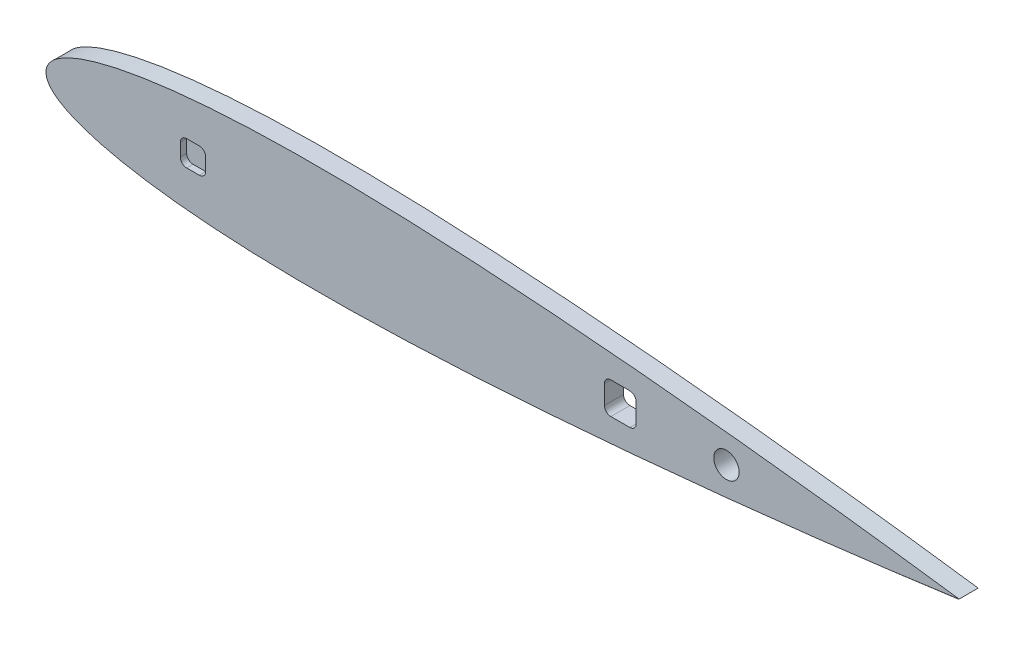
SolidWorks part; units mm, degrees
ref_plane "Plano frontal" through (0, 0, 0) normal (0, 0, 1) x (1, 0, 0)
ref_plane "Plano superior" through (0, 0, 0) normal (0, 1, 0) x (1, 0, 0)
ref_plane "Plano direito" through (0, 0, 0) normal (1, 0, 0) x (0, 0, -1)
curve "3"
  spline degree 3 poles (285.8178, -0.2472, 0) (289.2733, 0, 0) (285.8178, 0.2472, 0) (284.7679, 0.3981, 0) (284.2644, 0.4678, 0) (283.4377, 0.5838, 0) (282.2778, 0.7451, 0) (280.7932, 0.9499, 0) (278.9851, 1.1985, 0) (276.8584, 1.4881, 0) (274.4179, 1.8169, 0) (271.6694, 2.1836, 0) (268.6193, 2.5853, 0) (265.2747, 3.0204, 0) (261.6434, 3.4852, 0) (257.7338, 3.9787, 0) (253.5551, 4.4973, 0) (249.1172, 5.0383, 0) (244.4303, 5.5995, 0) (239.5054, 6.1777, 0) (234.3538, 6.7696, 0) (228.9879, 7.3736, 0) (223.4199, 7.9855, 0) (217.6632, 8.6035, 0) (211.7309, 9.2233, 0) (205.637, 9.8437, 0) (199.3956, 10.4599, 0) (193.0214, 11.07, 0) (186.5293, 11.6697, 0) (179.9344, 12.2571, 0) (173.2521, 12.8274, 0) (166.4979, 13.3779, 0) (159.6878, 13.9052, 0) (152.8376, 14.4051, 0) (145.9633, 14.8743, 0) (139.0811, 15.3092, 0) (132.2068, 15.7055, 0) (125.3566, 16.0601, 0) (118.5464, 16.3692, 0) (111.7921, 16.6293, 0) (105.1096, 16.8375, 0) (98.5145, 16.9901, 0) (92.0222, 17.0845, 0) (85.6476, 17.1179, 0) (79.4058, 17.0883, 0) (73.3113, 16.9946, 0) (67.3786, 16.8337, 0) (61.6212, 16.6065, 0) (56.0527, 16.3113, 0) (50.6859, 15.9489, 0) (45.5336, 15.5194, 0) (40.6077, 15.0237, 0) (35.9196, 14.4634, 0) (31.4802, 13.841, 0) (27.2999, 13.1577, 0) (23.3883, 12.4167, 0) (19.7544, 11.6209, 0) (16.4067, 10.7731, 0) (13.3526, 9.8769, 0) (10.5989, 8.9355, 0) (8.1513, 7.9519, 0) (6.0147, 6.9291, 0) (4.1933, 5.8692, 0) (2.6891, 4.774, 0) (1.5051, 3.6417, 0) (0.644, 2.4691, 0) (0.1176, 1.2504, 0) (-0.0573, 0, 0) (0.1176, -1.2504, 0) (0.644, -2.4691, 0) (1.5051, -3.6417, 0) (2.6891, -4.774, 0) (4.1933, -5.8692, 0) (6.0147, -6.9291, 0) (8.1513, -7.9519, 0) (10.5989, -8.9355, 0) (13.3526, -9.8769, 0) (16.4067, -10.7731, 0) (19.7544, -11.6209, 0) (23.3883, -12.4167, 0) (27.2999, -13.1577, 0) (31.4802, -13.841, 0) (35.9196, -14.4634, 0) (40.6077, -15.0237, 0) (45.5336, -15.5194, 0) (50.6859, -15.9489, 0) (56.0527, -16.3113, 0) (61.6212, -16.6065, 0) (67.3786, -16.8337, 0) (73.3113, -16.9946, 0) (79.4058, -17.0883, 0) (85.6476, -17.1179, 0) (92.0222, -17.0845, 0) (98.5145, -16.9901, 0) (105.1096, -16.8375, 0) (111.7921, -16.6293, 0) (118.5464, -16.3692, 0) (125.3566, -16.0601, 0) (132.2068, -15.7055, 0) (139.0811, -15.3092, 0) (145.9633, -14.8743, 0) (152.8376, -14.4051, 0) (159.6878, -13.9052, 0) (166.4979, -13.3779, 0) (173.2521, -12.8274, 0) (179.9344, -12.2571, 0) (186.5293, -11.6697, 0) (193.0214, -11.07, 0) (199.3956, -10.4599, 0) (205.637, -9.8437, 0) (211.7309, -9.2233, 0) (217.6632, -8.6035, 0) (223.4199, -7.9855, 0) (228.9879, -7.3736, 0) (234.3538, -6.7696, 0) (239.5054, -6.1777, 0) (244.4303, -5.5995, 0) (249.1172, -5.0383, 0) (253.5551, -4.4973, 0) (257.7338, -3.9787, 0) (261.6434, -3.4852, 0) (265.2747, -3.0204, 0) (268.6193, -2.5853, 0) (271.6694, -2.1836, 0) (274.4179, -1.8169, 0) (276.8584, -1.4881, 0) (278.9851, -1.1985, 0) (280.7932, -0.9499, 0) (282.2778, -0.7451, 0) (283.4377, -0.5838, 0) (284.2644, -0.4678, 0) (284.7679, -0.3981, 0) (285.8178, -0.2472, 0) (289.2733, 0, 0) (285.8178, 0.2472, 0) knots -0.00555 -0.004691 -0.004405 0 0.004405 0.004691 0.00555 0.00698 0.008976 0.011535 0.014649 0.018312 0.022515 0.027248 0.032498 0.038254 0.044502 0.051227 0.058413 0.066043 0.074099 0.082562 0.091412 0.100627 0.110187 0.120068 0.130247 0.140701 0.151404 0.162332 0.173459 0.184758 0.196204 0.207769 0.219426 0.231148 0.242906 0.254675 0.266426 0.278132 0.289766 0.301302 0.312712 0.323969 0.33505 0.345929 0.356581 0.366982 0.37711 0.386942 0.396458 0.405637 0.414459 0.422907 0.430963 0.438612 0.445838 0.45263 0.458976 0.464866 0.470294 0.475255 0.479749 0.483781 0.487363 0.490516 0.493279 0.495712 0.49791 0.5 0.50209 0.504288 0.506721 0.509484 0.512637 0.516219 0.520251 0.524745 0.529706 0.535134 0.541024 0.54737 0.554162 0.561388 0.569037 0.577093 0.585541 0.594363 0.603542 0.613058 0.62289 0.633018 0.643419 0.654071 0.66495 0.676031 0.687288 0.698698 0.710234 0.721868 0.733574 0.745325 0.757094 0.768852 0.780574 0.792231 0.803796 0.815242 0.826541 0.837668 0.848596 0.859299 0.869753 0.879932 0.889813 0.899373 0.908588 0.917438 0.925901 0.933957 0.941587 0.948773 0.955498 0.961746 0.967502 0.972752 0.977485 0.981688 0.985351 0.988465 0.991024 0.99302 0.99445 0.995309 0.995595 1 1.004405 1.004691 1.00555 periodic
curve "4"
  spline degree 3 poles (254.7117, -0.2203, 0) (257.7912, 0, 0) (254.7117, 0.2203, 0) (253.7761, 0.3548, 0) (253.3275, 0.4169, 0) (252.5907, 0.5202, 0) (251.5571, 0.664, 0) (250.234, 0.8465, 0) (248.6227, 1.068, 0) (246.7274, 1.3261, 0) (244.5525, 1.6192, 0) (242.1032, 1.9459, 0) (239.385, 2.304, 0) (236.4044, 2.6917, 0) (233.1683, 3.1059, 0) (229.6842, 3.5457, 0) (225.9603, 4.0078, 0) (222.0053, 4.49, 0) (217.8285, 4.9901, 0) (213.4396, 5.5054, 0) (208.8487, 6.0328, 0) (204.0667, 6.5711, 0) (199.1048, 7.1164, 0) (193.9746, 7.6672, 0) (188.6879, 8.2195, 0) (183.2571, 8.7724, 0) (177.695, 9.3215, 0) (172.0146, 9.8652, 0) (166.229, 10.3997, 0) (160.3518, 10.9232, 0) (154.3967, 11.4314, 0) (148.3777, 11.922, 0) (142.3087, 12.3919, 0) (136.204, 12.8373, 0) (130.0779, 13.2555, 0) (123.9447, 13.643, 0) (117.8185, 13.9962, 0) (111.7138, 14.3123, 0) (105.6448, 14.5877, 0) (99.6256, 14.8195, 0) (93.6704, 15.0051, 0) (87.793, 15.1411, 0) (82.0072, 15.2251, 0) (76.3264, 15.2549, 0) (70.7639, 15.2286, 0) (65.3327, 15.145, 0) (60.0456, 15.0017, 0) (54.9149, 14.7992, 0) (49.9524, 14.5361, 0) (45.1697, 14.2132, 0) (40.5781, 13.8304, 0) (36.1883, 13.3886, 0) (32.0104, 12.8893, 0) (28.0542, 12.3347, 0) (24.3288, 11.7257, 0) (20.8429, 11.0654, 0) (17.6045, 10.3562, 0) (14.6212, 9.6006, 0) (11.8994, 8.802, 0) (9.4454, 7.963, 0) (7.2642, 7.0865, 0) (5.3601, 6.175, 0) (3.7369, 5.2305, 0) (2.3965, 4.2545, 0) (1.3413, 3.2454, 0) (0.5739, 2.2004, 0) (0.1048, 1.1143, 0) (-0.0511, 0, 0) (0.1048, -1.1143, 0) (0.5739, -2.2004, 0) (1.3413, -3.2454, 0) (2.3965, -4.2545, 0) (3.7369, -5.2305, 0) (5.3601, -6.175, 0) (7.2642, -7.0865, 0) (9.4454, -7.963, 0) (11.8994, -8.802, 0) (14.6212, -9.6006, 0) (17.6045, -10.3562, 0) (20.8429, -11.0654, 0) (24.3288, -11.7257, 0) (28.0542, -12.3347, 0) (32.0104, -12.8893, 0) (36.1883, -13.3886, 0) (40.5781, -13.8304, 0) (45.1697, -14.2132, 0) (49.9524, -14.5361, 0) (54.9149, -14.7992, 0) (60.0456, -15.0017, 0) (65.3327, -15.145, 0) (70.7639, -15.2286, 0) (76.3264, -15.2549, 0) (82.0072, -15.2251, 0) (87.793, -15.1411, 0) (93.6704, -15.0051, 0) (99.6256, -14.8195, 0) (105.6448, -14.5877, 0) (111.7138, -14.3123, 0) (117.8185, -13.9962, 0) (123.9447, -13.643, 0) (130.0779, -13.2555, 0) (136.204, -12.8373, 0) (142.3087, -12.3919, 0) (148.3777, -11.922, 0) (154.3967, -11.4314, 0) (160.3518, -10.9232, 0) (166.229, -10.3997, 0) (172.0146, -9.8652, 0) (177.695, -9.3215, 0) (183.2571, -8.7724, 0) (188.6879, -8.2195, 0) (193.9746, -7.6672, 0) (199.1048, -7.1164, 0) (204.0667, -6.5711, 0) (208.8487, -6.0328, 0) (213.4396, -5.5054, 0) (217.8285, -4.9901, 0) (222.0053, -4.49, 0) (225.9603, -4.0078, 0) (229.6842, -3.5457, 0) (233.1683, -3.1059, 0) (236.4044, -2.6917, 0) (239.385, -2.304, 0) (242.1032, -1.9459, 0) (244.5525, -1.6192, 0) (246.7274, -1.3261, 0) (248.6227, -1.068, 0) (250.234, -0.8465, 0) (251.5571, -0.664, 0) (252.5907, -0.5202, 0) (253.3275, -0.4169, 0) (253.7761, -0.3548, 0) (254.7117, -0.2203, 0) (257.7912, 0, 0) (254.7117, 0.2203, 0) knots -0.00555 -0.004691 -0.004405 0 0.004405 0.004691 0.00555 0.00698 0.008976 0.011535 0.014649 0.018312 0.022515 0.027248 0.032498 0.038254 0.044502 0.051227 0.058413 0.066043 0.074099 0.082562 0.091412 0.100627 0.110187 0.120068 0.130247 0.140701 0.151404 0.162332 0.173459 0.184758 0.196204 0.207769 0.219426 0.231148 0.242906 0.254675 0.266426 0.278132 0.289766 0.301302 0.312712 0.323969 0.33505 0.345929 0.356581 0.366982 0.37711 0.386942 0.396458 0.405637 0.414459 0.422907 0.430963 0.438612 0.445838 0.45263 0.458976 0.464866 0.470294 0.475255 0.479749 0.483781 0.487363 0.490516 0.493279 0.495712 0.49791 0.5 0.50209 0.504288 0.506721 0.509484 0.512637 0.516219 0.520251 0.524745 0.529706 0.535134 0.541024 0.54737 0.554162 0.561388 0.569037 0.577093 0.585541 0.594363 0.603542 0.613058 0.62289 0.633018 0.643419 0.654071 0.66495 0.676031 0.687288 0.698698 0.710234 0.721868 0.733574 0.745325 0.757094 0.768852 0.780574 0.792231 0.803796 0.815242 0.826541 0.837668 0.848596 0.859299 0.869753 0.879932 0.889813 0.899373 0.908588 0.917438 0.925901 0.933957 0.941587 0.948773 0.955498 0.961746 0.967502 0.972752 0.977485 0.981688 0.985351 0.988465 0.991024 0.99302 0.99445 0.995309 0.995595 1 1.004405 1.004691 1.00555 periodic
sketch "3-4" plane through (0, 0, 0) normal (0, 0, 1) x (1, 0, 0)
  line L0 (287.6, 0) -> (256.3, 0) construction
  spline S0 degree 3 poles (254.7117, -0.2203) (257.7912, 0) (254.7117, 0.2203) (253.7761, 0.3548) (253.3275, 0.4169) (252.5907, 0.5202) (251.5571, 0.664) (250.234, 0.8465) (248.6227, 1.068) (246.7274, 1.3261) (244.5525, 1.6192) (242.1032, 1.9459) (239.385, 2.304) (236.4044, 2.6917) (233.1683, 3.1059) (229.6842, 3.5457) (225.9603, 4.0078) (222.0053, 4.49) (217.8285, 4.9901) (213.4396, 5.5054) (208.8487, 6.0328) (204.0667, 6.5711) (199.1048, 7.1164) (193.9746, 7.6672) (188.6879, 8.2195) (183.2571, 8.7724) (177.695, 9.3215) (172.0146, 9.8652) (166.229, 10.3997) (160.3518, 10.9232) (154.3967, 11.4314) (148.3777, 11.922) (142.3087, 12.3919) (136.204, 12.8373) (130.0779, 13.2555) (123.9447, 13.643) (117.8185, 13.9962) (111.7138, 14.3123) (105.6448, 14.5877) (99.6256, 14.8195) (93.6704, 15.0051) (87.793, 15.1411) (82.0072, 15.2251) (76.3264, 15.2549) (70.7639, 15.2286) (65.3327, 15.145) (60.0456, 15.0017) (54.9149, 14.7992) (49.9524, 14.5361) (45.1697, 14.2132) (40.5781, 13.8304) (36.1883, 13.3886) (32.0104, 12.8893) (28.0542, 12.3347) (24.3288, 11.7257) (20.8429, 11.0654) (17.6045, 10.3562) (14.6212, 9.6006) (11.8994, 8.802) (9.4454, 7.963) (7.2642, 7.0865) (5.3601, 6.175) (3.7369, 5.2305) (2.3965, 4.2545) (1.3413, 3.2454) (0.5739, 2.2004) (0.1048, 1.1143) (-0.0511, 0) (0.1048, -1.1143) (0.5739, -2.2004) (1.3413, -3.2454) (2.3965, -4.2545) (3.7369, -5.2305) (5.3601, -6.175) (7.2642, -7.0865) (9.4454, -7.963) (11.8994, -8.802) (14.6212, -9.6006) (17.6045, -10.3562) (20.8429, -11.0654) (24.3288, -11.7257) (28.0542, -12.3347) (32.0104, -12.8893) (36.1883, -13.3886) (40.5781, -13.8304) (45.1697, -14.2132) (49.9524, -14.5361) (54.9149, -14.7992) (60.0456, -15.0017) (65.3327, -15.145) (70.7639, -15.2286) (76.3264, -15.2549) (82.0072, -15.2251) (87.793, -15.1411) (93.6704, -15.0051) (99.6256, -14.8195) (105.6448, -14.5877) (111.7138, -14.3123) (117.8185, -13.9962) (123.9447, -13.643) (130.0779, -13.2555) (136.204, -12.8373) (142.3087, -12.3919) (148.3777, -11.922) (154.3967, -11.4314) (160.3518, -10.9232) (166.229, -10.3997) (172.0146, -9.8652) (177.695, -9.3215) (183.2571, -8.7724) (188.6879, -8.2195) (193.9746, -7.6672) (199.1048, -7.1164) (204.0667, -6.5711) (208.8487, -6.0328) (213.4396, -5.5054) (217.8285, -4.9901) (222.0053, -4.49) (225.9603, -4.0078) (229.6842, -3.5457) (233.1683, -3.1059) (236.4044, -2.6917) (239.385, -2.304) (242.1032, -1.9459) (244.5525, -1.6192) (246.7274, -1.3261) (248.6227, -1.068) (250.234, -0.8465) (251.5571, -0.664) (252.5907, -0.5202) (253.3275, -0.4169) (253.7761, -0.3548) (254.7117, -0.2203) (257.7912, 0) (254.7117, 0.2203) knots -0.00555 -0.004691 -0.004405 0 0.004405 0.004691 0.00555 0.00698 0.008976 0.011535 0.014649 0.018312 0.022515 0.027248 0.032498 0.038254 0.044502 0.051227 0.058413 0.066043 0.074099 0.082562 0.091412 0.100627 0.110187 0.120068 0.130247 0.140701 0.151404 0.162332 0.173459 0.184758 0.196204 0.207769 0.219426 0.231148 0.242906 0.254675 0.266426 0.278132 0.289766 0.301302 0.312712 0.323969 0.33505 0.345929 0.356581 0.366982 0.37711 0.386942 0.396458 0.405637 0.414459 0.422907 0.430963 0.438612 0.445838 0.45263 0.458976 0.464866 0.470294 0.475255 0.479749 0.483781 0.487363 0.490516 0.493279 0.495712 0.49791 0.5 0.50209 0.504288 0.506721 0.509484 0.512637 0.516219 0.520251 0.524745 0.529706 0.535134 0.541024 0.54737 0.554162 0.561388 0.569037 0.577093 0.585541 0.594363 0.603542 0.613058 0.62289 0.633018 0.643419 0.654071 0.66495 0.676031 0.687288 0.698698 0.710234 0.721868 0.733574 0.745325 0.757094 0.768852 0.780574 0.792231 0.803796 0.815242 0.826541 0.837668 0.848596 0.859299 0.869753 0.879932 0.889813 0.899373 0.908588 0.917438 0.925901 0.933957 0.941587 0.948773 0.955498 0.961746 0.967502 0.972752 0.977485 0.981688 0.985351 0.988465 0.991024 0.99302 0.99445 0.995309 0.995595 1 1.004405 1.004691 1.00555 only from (256.3, 0) to (256.3, 0) construction
  spline S1 degree 3 poles (285.8178, -0.2472) (289.2733, 0) (285.8178, 0.2472) (284.7679, 0.3981) (284.2644, 0.4678) (283.4377, 0.5838) (282.2778, 0.7451) (280.7932, 0.9499) (278.9851, 1.1985) (276.8584, 1.4881) (274.4179, 1.8169) (271.6694, 2.1836) (268.6193, 2.5853) (265.2747, 3.0204) (261.6434, 3.4852) (257.7338, 3.9787) (253.5551, 4.4973) (249.1172, 5.0383) (244.4303, 5.5995) (239.5054, 6.1777) (234.3538, 6.7696) (228.9879, 7.3736) (223.4199, 7.9855) (217.6632, 8.6035) (211.7309, 9.2233) (205.637, 9.8437) (199.3956, 10.4599) (193.0214, 11.07) (186.5293, 11.6697) (179.9344, 12.2571) (173.2521, 12.8274) (166.4979, 13.3779) (159.6878, 13.9052) (152.8376, 14.4051) (145.9633, 14.8743) (139.0811, 15.3092) (132.2068, 15.7055) (125.3566, 16.0601) (118.5464, 16.3692) (111.7921, 16.6293) (105.1096, 16.8375) (98.5145, 16.9901) (92.0222, 17.0845) (85.6476, 17.1179) (79.4058, 17.0883) (73.3113, 16.9946) (67.3786, 16.8337) (61.6212, 16.6065) (56.0527, 16.3113) (50.6859, 15.9489) (45.5336, 15.5194) (40.6077, 15.0237) (35.9196, 14.4634) (31.4802, 13.841) (27.2999, 13.1577) (23.3883, 12.4167) (19.7544, 11.6209) (16.4067, 10.7731) (13.3526, 9.8769) (10.5989, 8.9355) (8.1513, 7.9519) (6.0147, 6.9291) (4.1933, 5.8692) (2.6891, 4.774) (1.5051, 3.6417) (0.644, 2.4691) (0.1176, 1.2504) (-0.0573, 0) (0.1176, -1.2504) (0.644, -2.4691) (1.5051, -3.6417) (2.6891, -4.774) (4.1933, -5.8692) (6.0147, -6.9291) (8.1513, -7.9519) (10.5989, -8.9355) (13.3526, -9.8769) (16.4067, -10.7731) (19.7544, -11.6209) (23.3883, -12.4167) (27.2999, -13.1577) (31.4802, -13.841) (35.9196, -14.4634) (40.6077, -15.0237) (45.5336, -15.5194) (50.6859, -15.9489) (56.0527, -16.3113) (61.6212, -16.6065) (67.3786, -16.8337) (73.3113, -16.9946) (79.4058, -17.0883) (85.6476, -17.1179) (92.0222, -17.0845) (98.5145, -16.9901) (105.1096, -16.8375) (111.7921, -16.6293) (118.5464, -16.3692) (125.3566, -16.0601) (132.2068, -15.7055) (139.0811, -15.3092) (145.9633, -14.8743) (152.8376, -14.4051) (159.6878, -13.9052) (166.4979, -13.3779) (173.2521, -12.8274) (179.9344, -12.2571) (186.5293, -11.6697) (193.0214, -11.07) (199.3956, -10.4599) (205.637, -9.8437) (211.7309, -9.2233) (217.6632, -8.6035) (223.4199, -7.9855) (228.9879, -7.3736) (234.3538, -6.7696) (239.5054, -6.1777) (244.4303, -5.5995) (249.1172, -5.0383) (253.5551, -4.4973) (257.7338, -3.9787) (261.6434, -3.4852) (265.2747, -3.0204) (268.6193, -2.5853) (271.6694, -2.1836) (274.4179, -1.8169) (276.8584, -1.4881) (278.9851, -1.1985) (280.7932, -0.9499) (282.2778, -0.7451) (283.4377, -0.5838) (284.2644, -0.4678) (284.7679, -0.3981) (285.8178, -0.2472) (289.2733, 0) (285.8178, 0.2472) knots -0.00555 -0.004691 -0.004405 0 0.004405 0.004691 0.00555 0.00698 0.008976 0.011535 0.014649 0.018312 0.022515 0.027248 0.032498 0.038254 0.044502 0.051227 0.058413 0.066043 0.074099 0.082562 0.091412 0.100627 0.110187 0.120068 0.130247 0.140701 0.151404 0.162332 0.173459 0.184758 0.196204 0.207769 0.219426 0.231148 0.242906 0.254675 0.266426 0.278132 0.289766 0.301302 0.312712 0.323969 0.33505 0.345929 0.356581 0.366982 0.37711 0.386942 0.396458 0.405637 0.414459 0.422907 0.430963 0.438612 0.445838 0.45263 0.458976 0.464866 0.470294 0.475255 0.479749 0.483781 0.487363 0.490516 0.493279 0.495712 0.49791 0.5 0.50209 0.504288 0.506721 0.509484 0.512637 0.516219 0.520251 0.524745 0.529706 0.535134 0.541024 0.54737 0.554162 0.561388 0.569037 0.577093 0.585541 0.594363 0.603542 0.613058 0.62289 0.633018 0.643419 0.654071 0.66495 0.676031 0.687288 0.698698 0.710234 0.721868 0.733574 0.745325 0.757094 0.768852 0.780574 0.792231 0.803796 0.815242 0.826541 0.837668 0.848596 0.859299 0.869753 0.879932 0.889813 0.899373 0.908588 0.917438 0.925901 0.933957 0.941587 0.948773 0.955498 0.961746 0.967502 0.972752 0.977485 0.981688 0.985351 0.988465 0.991024 0.99302 0.99445 0.995309 0.995595 1 1.004405 1.004691 1.00555 only from (287.6, 0) to (287.6, 0) construction
  spline S2 degree 3 poles (254.7117, -0.2203) (257.7912, 0) (254.7117, 0.2203) (253.7761, 0.3548) (253.3275, 0.4169) (252.5907, 0.5202) (251.5571, 0.664) (250.234, 0.8465) (248.6227, 1.068) (246.7274, 1.3261) (244.5525, 1.6192) (242.1032, 1.9459) (239.385, 2.304) (236.4044, 2.6917) (233.1683, 3.1059) (229.6842, 3.5457) (225.9603, 4.0078) (222.0053, 4.49) (217.8285, 4.9901) (213.4396, 5.5054) (208.8487, 6.0328) (204.0667, 6.5711) (199.1048, 7.1164) (193.9746, 7.6672) (188.6879, 8.2195) (183.2571, 8.7724) (177.695, 9.3215) (172.0146, 9.8652) (166.229, 10.3997) (160.3518, 10.9232) (154.3967, 11.4314) (148.3777, 11.922) (142.3087, 12.3919) (136.204, 12.8373) (130.0779, 13.2555) (123.9447, 13.643) (117.8185, 13.9962) (111.7138, 14.3123) (105.6448, 14.5877) (99.6256, 14.8195) (93.6704, 15.0051) (87.793, 15.1411) (82.0072, 15.2251) (76.3264, 15.2549) (70.7639, 15.2286) (65.3327, 15.145) (60.0456, 15.0017) (54.9149, 14.7992) (49.9524, 14.5361) (45.1697, 14.2132) (40.5781, 13.8304) (36.1883, 13.3886) (32.0104, 12.8893) (28.0542, 12.3347) (24.3288, 11.7257) (20.8429, 11.0654) (17.6045, 10.3562) (14.6212, 9.6006) (11.8994, 8.802) (9.4454, 7.963) (7.2642, 7.0865) (5.3601, 6.175) (3.7369, 5.2305) (2.3965, 4.2545) (1.3413, 3.2454) (0.5739, 2.2004) (0.1048, 1.1143) (-0.0511, 0) (0.1048, -1.1143) (0.5739, -2.2004) (1.3413, -3.2454) (2.3965, -4.2545) (3.7369, -5.2305) (5.3601, -6.175) (7.2642, -7.0865) (9.4454, -7.963) (11.8994, -8.802) (14.6212, -9.6006) (17.6045, -10.3562) (20.8429, -11.0654) (24.3288, -11.7257) (28.0542, -12.3347) (32.0104, -12.8893) (36.1883, -13.3886) (40.5781, -13.8304) (45.1697, -14.2132) (49.9524, -14.5361) (54.9149, -14.7992) (60.0456, -15.0017) (65.3327, -15.145) (70.7639, -15.2286) (76.3264, -15.2549) (82.0072, -15.2251) (87.793, -15.1411) (93.6704, -15.0051) (99.6256, -14.8195) (105.6448, -14.5877) (111.7138, -14.3123) (117.8185, -13.9962) (123.9447, -13.643) (130.0779, -13.2555) (136.204, -12.8373) (142.3087, -12.3919) (148.3777, -11.922) (154.3967, -11.4314) (160.3518, -10.9232) (166.229, -10.3997) (172.0146, -9.8652) (177.695, -9.3215) (183.2571, -8.7724) (188.6879, -8.2195) (193.9746, -7.6672) (199.1048, -7.1164) (204.0667, -6.5711) (208.8487, -6.0328) (213.4396, -5.5054) (217.8285, -4.9901) (222.0053, -4.49) (225.9603, -4.0078) (229.6842, -3.5457) (233.1683, -3.1059) (236.4044, -2.6917) (239.385, -2.304) (242.1032, -1.9459) (244.5525, -1.6192) (246.7274, -1.3261) (248.6227, -1.068) (250.234, -0.8465) (251.5571, -0.664) (252.5907, -0.5202) (253.3275, -0.4169) (253.7761, -0.3548) (254.7117, -0.2203) (257.7912, 0) (254.7117, 0.2203) knots -0.00555 -0.004691 -0.004405 0 0.004405 0.004691 0.00555 0.00698 0.008976 0.011535 0.014649 0.018312 0.022515 0.027248 0.032498 0.038254 0.044502 0.051227 0.058413 0.066043 0.074099 0.082562 0.091412 0.100627 0.110187 0.120068 0.130247 0.140701 0.151404 0.162332 0.173459 0.184758 0.196204 0.207769 0.219426 0.231148 0.242906 0.254675 0.266426 0.278132 0.289766 0.301302 0.312712 0.323969 0.33505 0.345929 0.356581 0.366982 0.37711 0.386942 0.396458 0.405637 0.414459 0.422907 0.430963 0.438612 0.445838 0.45263 0.458976 0.464866 0.470294 0.475255 0.479749 0.483781 0.487363 0.490516 0.493279 0.495712 0.49791 0.5 0.50209 0.504288 0.506721 0.509484 0.512637 0.516219 0.520251 0.524745 0.529706 0.535134 0.541024 0.54737 0.554162 0.561388 0.569037 0.577093 0.585541 0.594363 0.603542 0.613058 0.62289 0.633018 0.643419 0.654071 0.66495 0.676031 0.687288 0.698698 0.710234 0.721868 0.733574 0.745325 0.757094 0.768852 0.780574 0.792231 0.803796 0.815242 0.826541 0.837668 0.848596 0.859299 0.869753 0.879932 0.889813 0.899373 0.908588 0.917438 0.925901 0.933957 0.941587 0.948773 0.955498 0.961746 0.967502 0.972752 0.977485 0.981688 0.985351 0.988465 0.991024 0.99302 0.99445 0.995309 0.995595 1 1.004405 1.004691 1.00555 only from (256.3, 0) to (256.3, 0)
  spline S3 degree 3 poles (285.8178, -0.2472) (289.2733, 0) (285.8178, 0.2472) (284.7679, 0.3981) (284.2644, 0.4678) (283.4377, 0.5838) (282.2778, 0.7451) (280.7932, 0.9499) (278.9851, 1.1985) (276.8584, 1.4881) (274.4179, 1.8169) (271.6694, 2.1836) (268.6193, 2.5853) (265.2747, 3.0204) (261.6434, 3.4852) (257.7338, 3.9787) (253.5551, 4.4973) (249.1172, 5.0383) (244.4303, 5.5995) (239.5054, 6.1777) (234.3538, 6.7696) (228.9879, 7.3736) (223.4199, 7.9855) (217.6632, 8.6035) (211.7309, 9.2233) (205.637, 9.8437) (199.3956, 10.4599) (193.0214, 11.07) (186.5293, 11.6697) (179.9344, 12.2571) (173.2521, 12.8274) (166.4979, 13.3779) (159.6878, 13.9052) (152.8376, 14.4051) (145.9633, 14.8743) (139.0811, 15.3092) (132.2068, 15.7055) (125.3566, 16.0601) (118.5464, 16.3692) (111.7921, 16.6293) (105.1096, 16.8375) (98.5145, 16.9901) (92.0222, 17.0845) (85.6476, 17.1179) (79.4058, 17.0883) (73.3113, 16.9946) (67.3786, 16.8337) (61.6212, 16.6065) (56.0527, 16.3113) (50.6859, 15.9489) (45.5336, 15.5194) (40.6077, 15.0237) (35.9196, 14.4634) (31.4802, 13.841) (27.2999, 13.1577) (23.3883, 12.4167) (19.7544, 11.6209) (16.4067, 10.7731) (13.3526, 9.8769) (10.5989, 8.9355) (8.1513, 7.9519) (6.0147, 6.9291) (4.1933, 5.8692) (2.6891, 4.774) (1.5051, 3.6417) (0.644, 2.4691) (0.1176, 1.2504) (-0.0573, 0) (0.1176, -1.2504) (0.644, -2.4691) (1.5051, -3.6417) (2.6891, -4.774) (4.1933, -5.8692) (6.0147, -6.9291) (8.1513, -7.9519) (10.5989, -8.9355) (13.3526, -9.8769) (16.4067, -10.7731) (19.7544, -11.6209) (23.3883, -12.4167) (27.2999, -13.1577) (31.4802, -13.841) (35.9196, -14.4634) (40.6077, -15.0237) (45.5336, -15.5194) (50.6859, -15.9489) (56.0527, -16.3113) (61.6212, -16.6065) (67.3786, -16.8337) (73.3113, -16.9946) (79.4058, -17.0883) (85.6476, -17.1179) (92.0222, -17.0845) (98.5145, -16.9901) (105.1096, -16.8375) (111.7921, -16.6293) (118.5464, -16.3692) (125.3566, -16.0601) (132.2068, -15.7055) (139.0811, -15.3092) (145.9633, -14.8743) (152.8376, -14.4051) (159.6878, -13.9052) (166.4979, -13.3779) (173.2521, -12.8274) (179.9344, -12.2571) (186.5293, -11.6697) (193.0214, -11.07) (199.3956, -10.4599) (205.637, -9.8437) (211.7309, -9.2233) (217.6632, -8.6035) (223.4199, -7.9855) (228.9879, -7.3736) (234.3538, -6.7696) (239.5054, -6.1777) (244.4303, -5.5995) (249.1172, -5.0383) (253.5551, -4.4973) (257.7338, -3.9787) (261.6434, -3.4852) (265.2747, -3.0204) (268.6193, -2.5853) (271.6694, -2.1836) (274.4179, -1.8169) (276.8584, -1.4881) (278.9851, -1.1985) (280.7932, -0.9499) (282.2778, -0.7451) (283.4377, -0.5838) (284.2644, -0.4678) (284.7679, -0.3981) (285.8178, -0.2472) (289.2733, 0) (285.8178, 0.2472) knots -0.00555 -0.004691 -0.004405 0 0.004405 0.004691 0.00555 0.00698 0.008976 0.011535 0.014649 0.018312 0.022515 0.027248 0.032498 0.038254 0.044502 0.051227 0.058413 0.066043 0.074099 0.082562 0.091412 0.100627 0.110187 0.120068 0.130247 0.140701 0.151404 0.162332 0.173459 0.184758 0.196204 0.207769 0.219426 0.231148 0.242906 0.254675 0.266426 0.278132 0.289766 0.301302 0.312712 0.323969 0.33505 0.345929 0.356581 0.366982 0.37711 0.386942 0.396458 0.405637 0.414459 0.422907 0.430963 0.438612 0.445838 0.45263 0.458976 0.464866 0.470294 0.475255 0.479749 0.483781 0.487363 0.490516 0.493279 0.495712 0.49791 0.5 0.50209 0.504288 0.506721 0.509484 0.512637 0.516219 0.520251 0.524745 0.529706 0.535134 0.541024 0.54737 0.554162 0.561388 0.569037 0.577093 0.585541 0.594363 0.603542 0.613058 0.62289 0.633018 0.643419 0.654071 0.66495 0.676031 0.687288 0.698698 0.710234 0.721868 0.733574 0.745325 0.757094 0.768852 0.780574 0.792231 0.803796 0.815242 0.826541 0.837668 0.848596 0.859299 0.869753 0.879932 0.889813 0.899373 0.908588 0.917438 0.925901 0.933957 0.941587 0.948773 0.955498 0.961746 0.967502 0.972752 0.977485 0.981688 0.985351 0.988465 0.991024 0.99302 0.99445 0.995309 0.995595 1 1.004405 1.004691 1.00555 only from (287.6, 0) to (287.6, 0)
  dimension "D1" = 31.3
sketch "Esboço2" plane through (0, 0, 0) normal (0, 0, 1) x (1, 0, 0)
  line L0 (287.6, 0) -> (180.9333, 0) construction
  line L1 (287.6, 0) -> (209.6, 0) construction
  line L2 (209.6, 0) -> (214.35, 0) construction
  line L3 (209.6, 0) -> (249.6, 0) construction
  line L5 (183.9333, -5) -> (177.9333, -5)
  line L6 (185.9333, -3) -> (185.9333, 3)
  line L7 (183.9333, 5) -> (177.9333, 5)
  line L8 (175.9333, -3) -> (175.9333, 3)
  line L9 (185.9333, -5) -> (175.9333, 5) construction
  line L10 (185.9333, 5) -> (175.9333, -5) construction
  circle A0 centre (214.35, 0) radius 4
  circle A1 centre (249.6, 0) radius 2.5 construction
  arc A2 (177.9333, -5) -> (175.9333, -3) centre (177.9333, -3) cw
  arc A3 (183.9333, -5) -> (185.9333, -3) centre (183.9333, -3) ccw
  arc A4 (185.9333, 3) -> (183.9333, 5) centre (183.9333, 3) ccw
  arc A5 (177.9333, 5) -> (175.9333, 3) centre (177.9333, 3) ccw
  arc A6 (209.6, 9.4393) -> (209.6, -9.4393) centre (215.0498, 0) ccw construction
  arc A7 (206.5968, 9.744) -> (206.5968, -9.744) centre (215.0498, 0) ccw construction
  arc A8 (208.6, 11.1714) -> (208.6, -11.1714) centre (215.0498, 0) ccw construction
  spline S0 degree 3 poles (285.8178, -0.2472) (289.2733, 0) (285.8178, 0.2472) (284.7679, 0.3981) (284.2644, 0.4678) (283.4377, 0.5838) (282.2778, 0.7451) (280.7932, 0.9499) (278.9851, 1.1985) (276.8584, 1.4881) (274.4179, 1.8169) (271.6694, 2.1836) (268.6193, 2.5853) (265.2747, 3.0204) (261.6434, 3.4852) (257.7338, 3.9787) (253.5551, 4.4973) (249.1172, 5.0383) (244.4303, 5.5995) (239.5054, 6.1777) (234.3538, 6.7696) (228.9879, 7.3736) (223.4199, 7.9855) (217.6632, 8.6035) (211.7309, 9.2233) (205.637, 9.8437) (199.3956, 10.4599) (193.0214, 11.07) (186.5293, 11.6697) (179.9344, 12.2571) (173.2521, 12.8274) (166.4979, 13.3779) (159.6878, 13.9052) (152.8376, 14.4051) (145.9633, 14.8743) (139.0811, 15.3092) (132.2068, 15.7055) (125.3566, 16.0601) (118.5464, 16.3692) (111.7921, 16.6293) (105.1096, 16.8375) (98.5145, 16.9901) (92.0222, 17.0845) (85.6476, 17.1179) (79.4058, 17.0883) (73.3113, 16.9946) (67.3786, 16.8337) (61.6212, 16.6065) (56.0527, 16.3113) (50.6859, 15.9489) (45.5336, 15.5194) (40.6077, 15.0237) (35.9196, 14.4634) (31.4802, 13.841) (27.2999, 13.1577) (23.3883, 12.4167) (19.7544, 11.6209) (16.4067, 10.7731) (13.3526, 9.8769) (10.5989, 8.9355) (8.1513, 7.9519) (6.0147, 6.9291) (4.1933, 5.8692) (2.6891, 4.774) (1.5051, 3.6417) (0.644, 2.4691) (0.1176, 1.2504) (-0.0573, 0) (0.1176, -1.2504) (0.644, -2.4691) (1.5051, -3.6417) (2.6891, -4.774) (4.1933, -5.8692) (6.0147, -6.9291) (8.1513, -7.9519) (10.5989, -8.9355) (13.3526, -9.8769) (16.4067, -10.7731) (19.7544, -11.6209) (23.3883, -12.4167) (27.2999, -13.1577) (31.4802, -13.841) (35.9196, -14.4634) (40.6077, -15.0237) (45.5336, -15.5194) (50.6859, -15.9489) (56.0527, -16.3113) (61.6212, -16.6065) (67.3786, -16.8337) (73.3113, -16.9946) (79.4058, -17.0883) (85.6476, -17.1179) (92.0222, -17.0845) (98.5145, -16.9901) (105.1096, -16.8375) (111.7921, -16.6293) (118.5464, -16.3692) (125.3566, -16.0601) (132.2068, -15.7055) (139.0811, -15.3092) (145.9633, -14.8743) (152.8376, -14.4051) (159.6878, -13.9052) (166.4979, -13.3779) (173.2521, -12.8274) (179.9344, -12.2571) (186.5293, -11.6697) (193.0214, -11.07) (199.3956, -10.4599) (205.637, -9.8437) (211.7309, -9.2233) (217.6632, -8.6035) (223.4199, -7.9855) (228.9879, -7.3736) (234.3538, -6.7696) (239.5054, -6.1777) (244.4303, -5.5995) (249.1172, -5.0383) (253.5551, -4.4973) (257.7338, -3.9787) (261.6434, -3.4852) (265.2747, -3.0204) (268.6193, -2.5853) (271.6694, -2.1836) (274.4179, -1.8169) (276.8584, -1.4881) (278.9851, -1.1985) (280.7932, -0.9499) (282.2778, -0.7451) (283.4377, -0.5838) (284.2644, -0.4678) (284.7679, -0.3981) (285.8178, -0.2472) (289.2733, 0) (285.8178, 0.2472) knots -0.00555 -0.004691 -0.004405 0 0.004405 0.004691 0.00555 0.00698 0.008976 0.011535 0.014649 0.018312 0.022515 0.027248 0.032498 0.038254 0.044502 0.051227 0.058413 0.066043 0.074099 0.082562 0.091412 0.100627 0.110187 0.120068 0.130247 0.140701 0.151404 0.162332 0.173459 0.184758 0.196204 0.207769 0.219426 0.231148 0.242906 0.254675 0.266426 0.278132 0.289766 0.301302 0.312712 0.323969 0.33505 0.345929 0.356581 0.366982 0.37711 0.386942 0.396458 0.405637 0.414459 0.422907 0.430963 0.438612 0.445838 0.45263 0.458976 0.464866 0.470294 0.475255 0.479749 0.483781 0.487363 0.490516 0.493279 0.495712 0.49791 0.5 0.50209 0.504288 0.506721 0.509484 0.512637 0.516219 0.520251 0.524745 0.529706 0.535134 0.541024 0.54737 0.554162 0.561388 0.569037 0.577093 0.585541 0.594363 0.603542 0.613058 0.62289 0.633018 0.643419 0.654071 0.66495 0.676031 0.687288 0.698698 0.710234 0.721868 0.733574 0.745325 0.757094 0.768852 0.780574 0.792231 0.803796 0.815242 0.826541 0.837668 0.848596 0.859299 0.869753 0.879932 0.889813 0.899373 0.908588 0.917438 0.925901 0.933957 0.941587 0.948773 0.955498 0.961746 0.967502 0.972752 0.977485 0.981688 0.985351 0.988465 0.991024 0.99302 0.99445 0.995309 0.995595 1 1.004405 1.004691 1.00555 only from (287.6, 0) to (287.6, 0) construction
  spline S1 degree 3 poles (285.8178, -0.2472) (289.2733, 0) (285.8178, 0.2472) (284.7679, 0.3981) (284.2644, 0.4678) (283.4377, 0.5838) (282.2778, 0.7451) (280.7932, 0.9499) (278.9851, 1.1985) (276.8584, 1.4881) (274.4179, 1.8169) (271.6694, 2.1836) (268.6193, 2.5853) (265.2747, 3.0204) (261.6434, 3.4852) (257.7338, 3.9787) (253.5551, 4.4973) (249.1172, 5.0383) (244.4303, 5.5995) (239.5054, 6.1777) (234.3538, 6.7696) (228.9879, 7.3736) (223.4199, 7.9855) (217.6632, 8.6035) (211.7309, 9.2233) (205.637, 9.8437) (199.3956, 10.4599) (193.0214, 11.07) (186.5293, 11.6697) (179.9344, 12.2571) (173.2521, 12.8274) (166.4979, 13.3779) (159.6878, 13.9052) (152.8376, 14.4051) (145.9633, 14.8743) (139.0811, 15.3092) (132.2068, 15.7055) (125.3566, 16.0601) (118.5464, 16.3692) (111.7921, 16.6293) (105.1096, 16.8375) (98.5145, 16.9901) (92.0222, 17.0845) (85.6476, 17.1179) (79.4058, 17.0883) (73.3113, 16.9946) (67.3786, 16.8337) (61.6212, 16.6065) (56.0527, 16.3113) (50.6859, 15.9489) (45.5336, 15.5194) (40.6077, 15.0237) (35.9196, 14.4634) (31.4802, 13.841) (27.2999, 13.1577) (23.3883, 12.4167) (19.7544, 11.6209) (16.4067, 10.7731) (13.3526, 9.8769) (10.5989, 8.9355) (8.1513, 7.9519) (6.0147, 6.9291) (4.1933, 5.8692) (2.6891, 4.774) (1.5051, 3.6417) (0.644, 2.4691) (0.1176, 1.2504) (-0.0573, 0) (0.1176, -1.2504) (0.644, -2.4691) (1.5051, -3.6417) (2.6891, -4.774) (4.1933, -5.8692) (6.0147, -6.9291) (8.1513, -7.9519) (10.5989, -8.9355) (13.3526, -9.8769) (16.4067, -10.7731) (19.7544, -11.6209) (23.3883, -12.4167) (27.2999, -13.1577) (31.4802, -13.841) (35.9196, -14.4634) (40.6077, -15.0237) (45.5336, -15.5194) (50.6859, -15.9489) (56.0527, -16.3113) (61.6212, -16.6065) (67.3786, -16.8337) (73.3113, -16.9946) (79.4058, -17.0883) (85.6476, -17.1179) (92.0222, -17.0845) (98.5145, -16.9901) (105.1096, -16.8375) (111.7921, -16.6293) (118.5464, -16.3692) (125.3566, -16.0601) (132.2068, -15.7055) (139.0811, -15.3092) (145.9633, -14.8743) (152.8376, -14.4051) (159.6878, -13.9052) (166.4979, -13.3779) (173.2521, -12.8274) (179.9344, -12.2571) (186.5293, -11.6697) (193.0214, -11.07) (199.3956, -10.4599) (205.637, -9.8437) (211.7309, -9.2233) (217.6632, -8.6035) (223.4199, -7.9855) (228.9879, -7.3736) (234.3538, -6.7696) (239.5054, -6.1777) (244.4303, -5.5995) (249.1172, -5.0383) (253.5551, -4.4973) (257.7338, -3.9787) (261.6434, -3.4852) (265.2747, -3.0204) (268.6193, -2.5853) (271.6694, -2.1836) (274.4179, -1.8169) (276.8584, -1.4881) (278.9851, -1.1985) (280.7932, -0.9499) (282.2778, -0.7451) (283.4377, -0.5838) (284.2644, -0.4678) (284.7679, -0.3981) (285.8178, -0.2472) (289.2733, 0) (285.8178, 0.2472) knots -0.00555 -0.004691 -0.004405 0 0.004405 0.004691 0.00555 0.00698 0.008976 0.011535 0.014649 0.018312 0.022515 0.027248 0.032498 0.038254 0.044502 0.051227 0.058413 0.066043 0.074099 0.082562 0.091412 0.100627 0.110187 0.120068 0.130247 0.140701 0.151404 0.162332 0.173459 0.184758 0.196204 0.207769 0.219426 0.231148 0.242906 0.254675 0.266426 0.278132 0.289766 0.301302 0.312712 0.323969 0.33505 0.345929 0.356581 0.366982 0.37711 0.386942 0.396458 0.405637 0.414459 0.422907 0.430963 0.438612 0.445838 0.45263 0.458976 0.464866 0.470294 0.475255 0.479749 0.483781 0.487363 0.490516 0.493279 0.495712 0.49791 0.5 0.50209 0.504288 0.506721 0.509484 0.512637 0.516219 0.520251 0.524745 0.529706 0.535134 0.541024 0.54737 0.554162 0.561388 0.569037 0.577093 0.585541 0.594363 0.603542 0.613058 0.62289 0.633018 0.643419 0.654071 0.66495 0.676031 0.687288 0.698698 0.710234 0.721868 0.733574 0.745325 0.757094 0.768852 0.780574 0.792231 0.803796 0.815242 0.826541 0.837668 0.848596 0.859299 0.869753 0.879932 0.889813 0.899373 0.908588 0.917438 0.925901 0.933957 0.941587 0.948773 0.955498 0.961746 0.967502 0.972752 0.977485 0.981688 0.985351 0.988465 0.991024 0.99302 0.99445 0.995309 0.995595 1 1.004405 1.004691 1.00555 only from (287.6, 0) to (287.6, 0)
  dimension "D2" = 8
  dimension "D4" = 5
  dimension "D9" = 2
  dimension "D1" = 4.75
  dimension "D3" = 40
  dimension "D5" = 78
  dimension "D6" = 106.6667
  dimension "D7" = 10
  dimension "D8" = 10
  dimension "D10" = 2
extrude "Ressalto-extrusão1" add sketch "Esboço2" along normal blind 6 contours A7 S1 A5 L7 A4 L6 A3 L5 A2 L8 | A6 S1 A0 A1
sketch "Esboço3" plane through (0, 0, 0) normal (0, 0, -1) x (-1, 0, 0)
  line L0 (0, 0) -> (-15, 0) construction
  line L2 (-13, -4) -> (-17, -4)
  line L3 (-11, -2) -> (-11, 2)
  line L4 (-13, 4) -> (-17, 4)
  line L5 (-19, -2) -> (-19, 2)
  line L6 (-11, -4) -> (-19, 4) construction
  line L7 (-11, 4) -> (-19, -4) construction
  arc A0 (-17, -4) -> (-19, -2) centre (-17, -2) cw
  arc A1 (-13, -4) -> (-11, -2) centre (-13, -2) ccw
  arc A2 (-11, 2) -> (-13, 4) centre (-13, 2) ccw
  arc A3 (-17, 4) -> (-19, 2) centre (-17, 2) ccw
  point P7 (-11, 0)
  dimension "D4" = 2
  dimension "D1" = 15
  dimension "D2" = 8
  dimension "D3" = 8
extrude "Corte-extrusão1" cut sketch "Esboço3" against normal blind 2
sketch "Esboço4" plane through (0, 0, 6) normal (0, 0, 1) x (1, 0, 0)
  line L0 (0, 0) -> (46.3, 0) construction
  line L2 (44.3, -4) -> (48.3, -4)
  line L3 (42.3, -2) -> (42.3, 2)
  line L4 (44.3, 4) -> (48.3, 4)
  line L5 (50.3, -2) -> (50.3, 2)
  line L6 (42.3, -4) -> (50.3, 4) construction
  line L7 (42.3, 4) -> (50.3, -4) construction
  arc A0 (44.3, -4) -> (42.3, -2) centre (44.3, -2) cw
  arc A1 (48.3, -4) -> (50.3, -2) centre (48.3, -2) ccw
  arc A2 (48.3, 4) -> (50.3, 2) centre (48.3, 2) cw
  arc A3 (42.3, 2) -> (44.3, 4) centre (44.3, 2) cw
  dimension "D4" = 2
  dimension "D1" = 46.3
  dimension "D2" = 8
  dimension "D3" = 8
extrude "Corte-extrusão2" cut sketch "Esboço4" against normal blind 2
